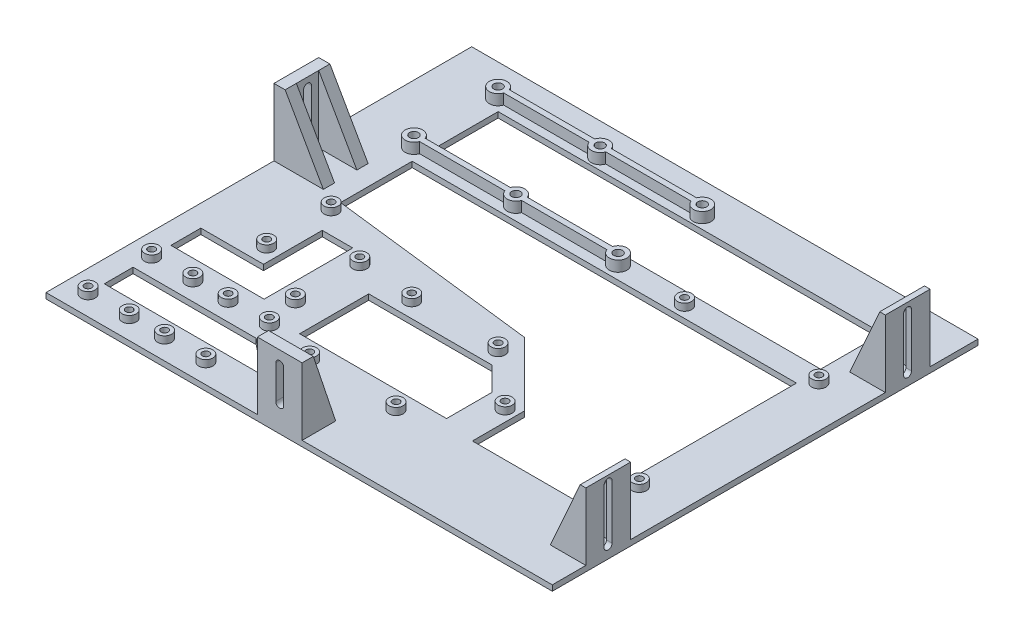
SolidWorks part; units mm, degrees
ref_plane "Front Plane" through (0, 0, 0) normal (0, 0, 1) x (1, 0, 0)
ref_plane "Top Plane" through (0, 0, 0) normal (0, 1, 0) x (1, 0, 0)
ref_plane "Right Plane" through (0, 0, 0) normal (1, 0, 0) x (0, 0, -1)
sketch "Sketch1" plane through (0, 0, 0) normal (0, 1, 0) x (1, 0, 0)
  line L1 (-143.637, -120.777) -> (143.637, -120.777)
  line L2 (-143.637, -120.777) -> (-143.637, 120.777)
  line L3 (-143.637, 120.777) -> (143.637, 120.777)
  line L4 (143.637, -120.777) -> (143.637, 120.777)
  line L5 (-143.637, -120.777) -> (143.637, 120.777) construction
  line L6 (-143.637, 120.777) -> (143.637, -120.777) construction
  point P0 (0, 0)
  dimension "D1" = 287.274
  dimension "D2" = 241.554
extrude "Boss-Extrude1" add sketch "Sketch1" along normal blind 3.175
sketch "Sketch2" plane through (0, 3.175, 0) normal (0, 1, 0) x (1, 0, 0)
  line L0 (-143.637, 93.599) -> (-143.637, 68.199)
  line L2 (-140.462, 93.599) -> (-143.637, 93.599)
  line L6 (-140.462, 68.199) -> (-140.462, 93.599)
  line L7 (-146.812, 68.199) -> (-140.462, 93.599) construction
  line L8 (-146.812, 93.599) -> (-140.462, 68.199) construction
  line L9 (-140.462, 68.199) -> (-143.637, 68.199)
  line L10 (0, 120.777) -> (0, 106.0603)
  line L11 (143.637, 120.777) -> (-143.637, 120.777) construction
  line L12 (146.812, 93.599) -> (140.462, 68.199) construction
  line L13 (146.812, 68.199) -> (140.462, 93.599) construction
  line L14 (140.462, 68.199) -> (143.637, 68.199)
  line L15 (140.462, 68.199) -> (140.462, 93.599)
  line L16 (140.462, 93.599) -> (143.637, 93.599)
  line L17 (143.637, 93.599) -> (143.637, 68.199)
  line M6 (143.637, -120.777) -> (143.637, 120.777)
  dimension "D2" = 25.4
  dimension "D3" = 6.35
extrude "Boss-Extrude3" add sketch "Sketch2" along normal blind 38.1 contours L16 L15 L14 M6
sketch "Sketch3" plane through (140.462, 0, 0) normal (-1, 0, 0) x (0, 0, 1)
  line L0 (-80.808, 36.6569) -> (-80.808, 6.3832) construction
  line L1 (-78.558, 36.6569) -> (-78.558, 6.3832)
  line L2 (-83.058, 36.6569) -> (-83.058, 6.3832)
  line L5 (-93.599, 41.275) -> (-93.599, 3.175) construction
  arc A0 (-78.558, 36.6569) -> (-83.058, 36.6569) centre (-80.808, 36.6569) ccw
  arc A1 (-83.058, 6.3832) -> (-78.558, 6.3832) centre (-80.808, 6.3832) ccw
  point P2 (-80.808, 21.5201)
  dimension "D1" = 4.5
  dimension "D2" = 10.541
extrude "Cut-Extrude1" cut sketch "Sketch3" against normal blind 25.4 contours L2 A1 L1 A0
sketch "Sketch4" plane through (0, 3.175, 0) normal (0, 1, 0) x (1, 0, 0)
  line L5 (39.497, -52.197) -> (124.587, 58.293) construction
  line L6 (39.497, 58.293) -> (124.587, -52.197) construction
  line L8 (82.042, 57.277) -> (82.042, 44.8097)
  line L9 (39.497, 3.048) -> (51.5322, 3.048)
  circle A0 centre (120.142, 53.975) radius 2
  circle A1 centre (120.142, 53.975) radius 4
  circle A2 centre (43.942, 53.975) radius 4
  circle A3 centre (43.942, 53.975) radius 2
  circle A4 centre (43.942, -47.879) radius 2
  circle A5 centre (43.942, -47.879) radius 4
  circle A6 centre (120.142, -47.879) radius 4
  circle A7 centre (120.142, -47.879) radius 2
  point P0 (82.042, 3.048)
  dimension "D5" = 8
  dimension "D6" = 4
  dimension "D7" = 4
  dimension "D1" = 76.2
  dimension "D2" = 101.854
  dimension "D3" = 110.49
  dimension "D4" = 85.09
extrude "Boss-Extrude4" add sketch "Sketch4" along normal blind 4 contours A2 A3 | A1 A0 | A5 A4 | A6 A7
sketch "Sketch5" plane through (0, 3.175, 0) normal (0, 1, 0) x (1, 0, 0)
  line L0 (143.637, 103.4969) -> (5.207, 103.4969)
  line L1 (143.637, 93.599) -> (143.637, 120.777) construction
  line L2 (5.207, 120.777) -> (5.207, 102.743)
  line L3 (143.637, 120.777) -> (-143.637, 120.777) construction
  circle A0 centre (5.207, 102.743) radius 2.5
  circle A1 centre (5.207, 102.743) radius 5
  circle A2 centre (5.207, 54.991) radius 2.5
  circle A3 centre (5.207, 54.991) radius 5
  circle A4 centre (-52.705, 54.991) radius 5
  circle A5 centre (-52.705, 54.991) radius 2.5
  circle A6 centre (-52.705, 102.743) radius 5
  circle A7 centre (-52.705, 102.743) radius 2.5
  circle A8 centre (-110.617, 54.991) radius 2.5
  circle A9 centre (-110.617, 54.991) radius 5
  circle A10 centre (-110.617, 102.743) radius 2.5
  circle A11 centre (-110.617, 102.743) radius 5
  dimension "D3" = 5
  dimension "D4" = 10
  dimension "D5" = 47.752
  dimension "D6" = 5
  dimension "D7" = 10
  dimension "D8" = 57.912
  dimension "D9" = 5
  dimension "D10" = 10
  dimension "D11" = 5
  dimension "D12" = 10
  dimension "D13" = 57.912
  dimension "D14" = 5
  dimension "D15" = 10
  dimension "D16" = 5
  dimension "D17" = 10
  dimension "D1" = 138.43
  dimension "D2" = 18.034
extrude "Boss-Extrude5" add sketch "Sketch5" along normal blind 6 contours A11 A10 | A6 A7 | L0 A1 L2 A0 | L2 A1 L0 A0 | A9 A8 | A4 A5 | A3 A2
sketch "Sketch6" plane through (0, 3.175, 0) normal (0, 1, 0) x (1, 0, 0)
  line L0 (-143.637, 120.777) -> (-143.637, -120.777) construction
  line L1 (-143.637, -120.777) -> (143.637, -120.777) construction
  circle A0 centre (-130.937, -109.601) radius 2
  circle A1 centre (-107.569, -109.601) radius 2
  circle A2 centre (-130.937, -73.533) radius 2
  circle A3 centre (-107.569, -73.533) radius 2
  circle A4 centre (-130.937, -73.533) radius 4
  circle A5 centre (-107.569, -73.533) radius 4
  circle A6 centre (-130.937, -109.601) radius 4
  circle A7 centre (-107.569, -109.601) radius 4
  circle A8 centre (-87.503, -109.601) radius 2
  circle A9 centre (-64.135, -109.601) radius 2
  circle A10 centre (-87.503, -73.533) radius 2
  circle A11 centre (-64.135, -73.533) radius 2
  circle A12 centre (-87.503, -73.533) radius 4
  circle A13 centre (-64.135, -73.533) radius 4
  circle A14 centre (-87.503, -109.601) radius 4
  circle A15 centre (-64.135, -109.601) radius 4
  dimension "D1" = 12.7
  dimension "D2" = 11.176
  dimension "D3" = 23.368
  dimension "D4" = 11.176
  dimension "D5" = 36.068
  dimension "D7" = 23.368
  dimension "D8" = 36.068
  dimension "D9" = 4
  dimension "D10" = 4
  dimension "D11" = 4
  dimension "D12" = 4
  dimension "D13" = 8
  dimension "D14" = 8
  dimension "D15" = 8
  dimension "D16" = 8
  dimension "D21" = 4
  dimension "D22" = 4
  dimension "D23" = 4
  dimension "D24" = 4
  dimension "D25" = 8
  dimension "D26" = 8
  dimension "D27" = 8
  dimension "D28" = 8
  dimension "D29" = 20.066
  dimension "D30" = 0
  dimension "D31" = 0
  dimension "D6" = 12.7
  dimension "D17" = 23.368
  dimension "D18" = 36.068
  dimension "D19" = 23.368
  dimension "D20" = 36.068
extrude "Boss-Extrude6" add sketch "Sketch6" along normal blind 4 contours A4 | A2 | A5 | A3 | A12 | A10 | A13 | A11 | A6 | A0 | A7 | A1 | A14 | A8 | A15 | A9
sketch "Sketch7" plane through (0, 3.175, 0) normal (0, 1, 0) x (1, 0, 0)
  line L0 (-143.637, 120.777) -> (-143.637, -120.777) construction
  line L1 (-143.637, -120.777) -> (143.637, -120.777) construction
  circle A0 centre (-103.251, -35.941) radius 2
  circle A1 centre (-68.199, -54.737) radius 2
  circle A2 centre (-103.251, -35.941) radius 4
  circle A3 centre (-68.199, -54.737) radius 4
  circle A4 centre (-103.251, 0.635) radius 2
  circle A5 centre (-68.199, -18.161) radius 2
  circle A6 centre (-103.251, 0.635) radius 4
  circle A7 centre (-68.199, -18.161) radius 4
  dimension "D1" = 40.386
  dimension "D2" = 84.836
  dimension "D3" = 4
  dimension "D4" = 66.04
  dimension "D5" = 75.438
  dimension "D6" = 4
  dimension "D7" = 8
  dimension "D8" = 8
  dimension "D9" = 36.576
  dimension "D10" = 0
  dimension "D11" = 36.576
  dimension "D12" = 0
  dimension "D13" = 4
  dimension "3MM" = 4
  dimension "D14" = 8
  dimension "D15" = 8
  dimension "D16" = 4
extrude "Boss-Extrude7" add sketch "Sketch7" along normal blind 4
sketch "Sketch8" plane through (0, 3.175, 0) normal (0, 1, 0) x (1, 0, 0)
  line L0 (-143.637, 120.777) -> (-143.637, -120.777) construction
  line L1 (-143.637, -120.777) -> (143.637, -120.777) construction
  circle A0 centre (-35.687, -21.209) radius 2
  circle A1 centre (13.335, -21.209) radius 2
  circle A2 centre (-35.687, -79.121) radius 2
  circle A3 centre (13.335, -79.121) radius 2
  circle A4 centre (-35.687, -21.209) radius 4
  circle A5 centre (13.335, -21.209) radius 4
  circle A6 centre (-35.687, -79.121) radius 4
  circle A7 centre (13.335, -79.121) radius 4
  dimension "D1" = 107.95
  dimension "D2" = 57.912
  dimension "D3" = 41.656
  dimension "D4" = 49.022
  dimension "D5" = 0
  dimension "D6" = 0
  dimension "D7" = 0
  dimension "D8" = 4
  dimension "D9" = 4
  dimension "D10" = 4
  dimension "D11" = 4
  dimension "D12" = 8
  dimension "D13" = 8
  dimension "D14" = 8
  dimension "D15" = 8
  dimension "D16" = 49.022
extrude "Boss-Extrude8" add sketch "Sketch8" along normal blind 4
sketch "Sketch9" plane through (0, 3.175, 0) normal (0, 1, 0) x (1, 0, 0)
  line L0 (143.637, -76.327) -> (143.637, -101.727)
  line L4 (140.462, -101.727) -> (140.462, -76.327)
  line L7 (-143.637, -120.777) -> (143.637, -120.777) construction
  line L9 (140.462, -76.327) -> (143.637, -76.327)
  line L10 (140.462, -101.727) -> (143.637, -101.727)
  dimension "D1" = 25.4
  dimension "D2" = 19.05
extrude "Boss-Extrude9" add sketch "Sketch9" along normal blind 38.1
sketch "Sketch13" plane through (140.462, 0, 0) normal (-1, 0, 0) x (0, 0, 1)
  line L0 (89.118, 37.4464) -> (89.118, 6.7099) construction
  line L1 (91.368, 37.4464) -> (91.368, 6.7099)
  line L2 (86.868, 37.4464) -> (86.868, 6.7099)
  line L3 (76.327, 41.275) -> (76.327, 3.175) construction
  arc A0 (91.368, 37.4464) -> (86.868, 37.4464) centre (89.118, 37.4464) ccw
  arc A1 (86.868, 6.7099) -> (91.368, 6.7099) centre (89.118, 6.7099) ccw
  point P2 (89.118, 22.0781)
  dimension "D1" = 4.5
  dimension "D2" = 10.541
extrude "Cut-Extrude3" cut sketch "Sketch13" against normal blind 38.1
sketch "Sketch17" plane through (0, 0, -93.599) normal (0, 0, -1) x (-1, 0, 0)
  line L0 (-140.462, 41.275) -> (-124.142, 3.175)
  line L1 (-124.142, 3.175) -> (-127.216, 3.175)
  line L2 (-143.637, 3.175) -> (143.637, 3.175) construction
  line L4 (-140.462, 41.275) -> (-140.462, 3.175) construction
  line L5 (-140.462, 32.8303) -> (-140.462, 41.275)
  line L6 (-140.462, 32.8303) -> (-140.462, 3.175)
  line L7 (-140.462, 3.175) -> (-127.216, 3.175)
extrude "Boss-Extrude11" add sketch "Sketch17" against normal blind 6.35
sketch "Sketch22" plane through (0, 0, 76.327) normal (0, 0, -1) x (-1, 0, 0)
  line L0 (-140.462, 41.275) -> (-123.444, 3.175)
  line L1 (-123.444, 3.175) -> (-127.216, 3.175)
  line L3 (-140.462, 32.8303) -> (-140.462, 41.275)
  line L4 (-140.462, 32.8303) -> (-140.462, 3.175)
  line L5 (-143.637, 3.175) -> (-140.462, 3.175) construction
  line L6 (-140.462, 41.275) -> (-140.462, 3.175) construction
  line L7 (-127.216, 3.175) -> (-140.462, 3.175)
extrude "Boss-Extrude12" add sketch "Sketch22" against normal blind 6.35
sketch "Sketch23" plane through (0, 0, -68.199) normal (0, 0, 1) x (1, 0, 0)
  line L0 (140.462, 41.275) -> (123.444, 3.175)
  line L1 (123.444, 3.175) -> (127.216, 3.175)
  line L3 (140.462, 32.8303) -> (140.462, 41.275)
  line L4 (127.216, 3.175) -> (140.462, 3.175)
  line L5 (140.462, 3.175) -> (140.462, 32.8303)
extrude "Boss-Extrude13" add sketch "Sketch23" against normal blind 6.35
sketch "Sketch34" plane through (0, 3.175, 0) normal (0, 1, 0) x (1, 0, 0)
  line L4 (-104.267, 96.393) -> (-104.267, 61.341)
  line L12 (113.792, 96.393) -> (113.792, 61.341)
  line L13 (-104.267, 96.393) -> (113.792, 96.393)
  line L34 (-104.267, 61.341) -> (113.792, 61.341)
  line L37 (-104.267, 47.625) -> (113.792, 47.625)
  line L38 (-104.267, 47.625) -> (-104.267, 6.985)
  line L40 (113.792, 47.625) -> (113.792, 6.985)
  line L41 (113.792, -54.229) -> (113.792, 6.985)
  line L45 (113.792, -54.229) -> (113.792, -72.771)
  line L46 (50.292, -54.229) -> (50.292, -43.2308)
  line L47 (50.292, -54.229) -> (50.292, -72.771)
  line L48 (50.292, -72.771) -> (113.792, -72.771)
  line L50 (50.292, -43.2308) -> (14.1231, -7.0619)
  line L51 (14.1231, -7.0619) -> (-104.267, 6.985)
  line L52 (-51.4249, -29.8851) -> (-51.4249, -69.0875)
  line L53 (-51.4249, -69.0875) -> (31.9418, -69.0875)
  line L54 (31.9418, -69.0875) -> (31.9418, -43.2308)
  line L55 (31.9418, -43.2308) -> (18.5961, -29.8851)
  line L56 (18.5961, -29.8851) -> (-51.4249, -29.8851)
  circle A0 centre (120.142, 53.975) radius 2 construction
  circle A1 centre (-110.617, 54.991) radius 2.5 construction
  circle A2 centre (43.942, 53.975) radius 2 construction
  circle A6 centre (43.942, -47.879) radius 2 construction
  circle A9 centre (-103.251, 0.635) radius 2 construction
  dimension "D3" = 0
  dimension "D6" = 6.35
  dimension "D5" = 1.016
  dimension "D12" = 6.35
  dimension "D1" = 0
  dimension "D2" = 6.35
  dimension "D7" = 6.35
  dimension "D8" = 0
extrude "Cut-Extrude10" cut sketch "Sketch34" against normal through all
sketch "Sketch35" plane through (0, 0, 101.727) normal (0, 0, 1) x (1, 0, 0)
  line L0 (140.462, 41.275) -> (140.462, 3.175)
  line L1 (140.462, 3.175) -> (123.444, 3.175)
  line L2 (123.444, 3.175) -> (140.462, 41.275)
  dimension "D1" = 17.018
sketch "Sketch37" plane through (0, 0, 101.727) normal (0, 0, 1) x (1, 0, 0)
  line L0 (140.462, 41.275) -> (123.444, 3.175)
  line L1 (123.444, 3.175) -> (140.462, 3.175)
  line L2 (140.462, 3.175) -> (140.462, 41.275)
extrude "Boss-Extrude14" add sketch "Sketch37" against normal blind 6.35
sketch "Sketch40" plane through (0, 3.175, 0) normal (0, 1, 0) x (1, 0, 0)
  line L0 (-104.267, 78.867) -> (-113.7757, 78.867)
  line L2 (-104.267, 96.393) -> (-104.267, 61.341) construction
  line L4 (1.707, 104.3305) -> (-107.117, 104.3305)
  line L5 (1.707, 101.1555) -> (-107.117, 101.1555)
  line L6 (1.707, 56.5785) -> (-107.117, 56.5785)
  line L7 (1.707, 53.4035) -> (-107.117, 53.4035)
  line L8 (1.707, 56.5785) -> (1.707, 53.4035)
  line L9 (-107.117, 56.5785) -> (-107.117, 53.4035)
  line L10 (-107.117, 104.3305) -> (-107.117, 101.1555)
  line L11 (1.707, 104.3305) -> (1.707, 101.1555)
  circle A0 centre (-110.617, 102.743) radius 2.5 construction
  point P9 (-107.117, 53.3454)
  point P11 (1.707, 53.3454)
  point P24 (1.707, 104.3886)
  point P25 (-107.117, 104.3886)
  dimension "D1" = 3.175
  dimension "D2" = 1.5875
extrude "Boss-Extrude15" add sketch "Sketch40" along normal blind 6
sketch "Sketch41" plane through (0, 9.175, 0) normal (0, 1, 0) x (1, 0, 0)
  circle A0 centre (-52.705, 54.991) radius 2.5
  circle A1 centre (-52.705, 102.743) radius 2.5
extrude "Cut-Extrude13" cut sketch "Sketch41" against normal up to surface (6 mm away) up to face at (-4.074, 3.175, 48.2352)
sketch "Sketch43" plane through (0, 3.175, 0) normal (0, 1, 0) x (1, 0, 0)
  line L0 (-143.637, 120.777) -> (-143.637, -120.777) construction
  line L1 (-143.637, 33.9735) -> (-137.287, 33.9735)
  line L2 (-143.637, 33.9735) -> (-143.637, 8.5735)
  line L3 (-143.637, 8.5735) -> (-137.287, 8.5735)
  line L4 (-137.287, 33.9735) -> (-137.287, 8.5735)
  dimension "D1" = 25.4
  dimension "D2" = 6.35
extrude "Boss-Extrude16" add sketch "Sketch43" along normal blind 38.1
sketch "Sketch45" plane through (0, 0, -8.5735) normal (0, 0, 1) x (1, 0, 0)
  line L0 (-137.287, 41.275) -> (-115.617, 3.175)
  line L1 (-115.617, 3.175) -> (-137.287, 3.175)
  line L2 (-137.287, 3.175) -> (-137.287, 41.275)
extrude "Boss-Extrude17" add sketch "Sketch45" against normal blind 25.4
sketch "Sketch46" plane through (0, 41.275, 0) normal (0, 1, 0) x (1, 0, 0)
  line L0 (-137.287, 8.5735) -> (-137.287, 33.9735) construction
  line L1 (-137.287, 27.6235) -> (-115.617, 27.6235)
  line L2 (-137.287, 27.6235) -> (-137.287, 14.9235)
  line L3 (-137.287, 14.9235) -> (-115.617, 14.9235)
  line L4 (-115.617, 27.6235) -> (-115.617, 14.9235)
  line L5 (-115.617, 33.9735) -> (-115.617, 8.5735) construction
  line L6 (-115.617, 33.9735) -> (-143.637, 33.9735) construction
  line L7 (-143.637, 8.5735) -> (-115.617, 8.5735) construction
  dimension "D1" = 6.35
  dimension "D2" = 6.35
extrude "Cut-Extrude14" cut sketch "Sketch46" against normal blind 38.1
sketch "Sketch47" plane through (-143.637, 0, 0) normal (-1, 0, 0) x (0, 0, 1)
  line L0 (-21.2735, 35.9208) -> (-21.2735, 10.5208) construction
  line L1 (-19.0235, 35.9208) -> (-19.0235, 10.5208)
  line L2 (-23.5235, 35.9208) -> (-23.5235, 10.5208)
  line L3 (-33.9735, 41.275) -> (-33.9735, 3.175) construction
  arc A0 (-19.0235, 35.9208) -> (-23.5235, 35.9208) centre (-21.2735, 35.9208) ccw
  arc A1 (-23.5235, 10.5208) -> (-19.0235, 10.5208) centre (-21.2735, 10.5208) ccw
  point P2 (-21.2735, 23.2208)
  dimension "D1" = 12.7
extrude "Cut-Extrude15" cut sketch "Sketch47" against normal blind 38.1
sketch "Sketch48" plane through (0, 3.175, 0) normal (0, 1, 0) x (1, 0, 0)
  line L0 (-143.637, -120.777) -> (143.637, -120.777) construction
  line L1 (-23.7167, -120.777) -> (1.6833, -120.777)
  line L2 (-23.7167, -120.777) -> (-23.7167, -114.427)
  line L3 (-23.7167, -114.427) -> (1.6833, -114.427)
  line L4 (1.6833, -120.777) -> (1.6833, -114.427)
  dimension "D1" = 25.4
  dimension "D2" = 6.35
extrude "Boss-Extrude18" add sketch "Sketch48" along normal blind 38.1
sketch "Sketch49" plane through (1.6833, 0, 0) normal (1, 0, 0) x (0, 0, -1)
  line L0 (-114.427, 41.275) -> (-101.727, 3.175)
  line L1 (-101.727, 3.175) -> (-114.427, 3.175)
  line L2 (-114.427, 3.175) -> (-114.427, 41.275)
extrude "Boss-Extrude19" add sketch "Sketch49" against normal blind 25.4
sketch "Sketch50" plane through (0, 41.275, 0) normal (0, 1, 0) x (1, 0, 0)
  line L0 (1.6833, -114.427) -> (-23.7167, -114.427) construction
  line L1 (-17.3667, -114.427) -> (-4.6667, -114.427)
  line L2 (-17.3667, -114.427) -> (-17.3667, -101.727)
  line L3 (-17.3667, -101.727) -> (-4.6667, -101.727)
  line L4 (-4.6667, -114.427) -> (-4.6667, -101.727)
  line L5 (-23.7167, -101.727) -> (1.6833, -101.727) construction
  line L6 (-23.7167, -101.727) -> (-23.7167, -114.427) construction
  line L7 (1.6833, -101.727) -> (1.6833, -114.427) construction
  dimension "D1" = 6.35
  dimension "D2" = 6.35
extrude "Cut-Extrude16" cut sketch "Sketch50" against normal blind 38.1
sketch "Sketch51" plane through (0, 0, 120.777) normal (0, 0, 1) x (1, 0, 0)
  line L0 (-11.0167, 33.7836) -> (-11.0167, 14.8771) construction
  line L1 (-8.7667, 33.7836) -> (-8.7667, 14.8771)
  line L2 (-13.2667, 33.7836) -> (-13.2667, 14.8771)
  line L3 (-23.7167, 41.275) -> (-23.7167, 3.175) construction
  arc A0 (-8.7667, 33.7836) -> (-13.2667, 33.7836) centre (-11.0167, 33.7836) ccw
  arc A1 (-13.2667, 14.8771) -> (-8.7667, 14.8771) centre (-11.0167, 14.8771) ccw
  point P2 (-11.0167, 24.3303)
  dimension "D2" = 12.7
extrude "Cut-Extrude17" cut sketch "Sketch51" against normal blind 38.1
sketch "Sketch52" plane through (0, 3.175, 0) normal (0, 1, 0) x (1, 0, 0)
  line L0 (-95.8067, -11.8557) -> (-78.5038, -11.8557)
  line L1 (-78.5038, -11.8557) -> (-78.5038, -62.1622)
  line L2 (-78.5038, -62.1622) -> (-131.3738, -62.1622)
  line L3 (-131.3738, -62.1622) -> (-131.3738, -45.1798)
  line L4 (-131.3738, -45.1798) -> (-95.8067, -45.1798)
  line L5 (-95.8067, -45.1798) -> (-95.8067, -11.8557)
  line L6 (-131.3738, -83.6306) -> (-131.3738, -99.9722)
  line L7 (-131.3738, -99.9722) -> (-41.0142, -99.9722)
  line L8 (-41.0142, -99.9722) -> (-61.5214, -83.6306)
  line L9 (-61.5214, -83.6306) -> (-131.3738, -83.6306)
extrude "Cut-Extrude18" cut sketch "Sketch52" against normal through all
